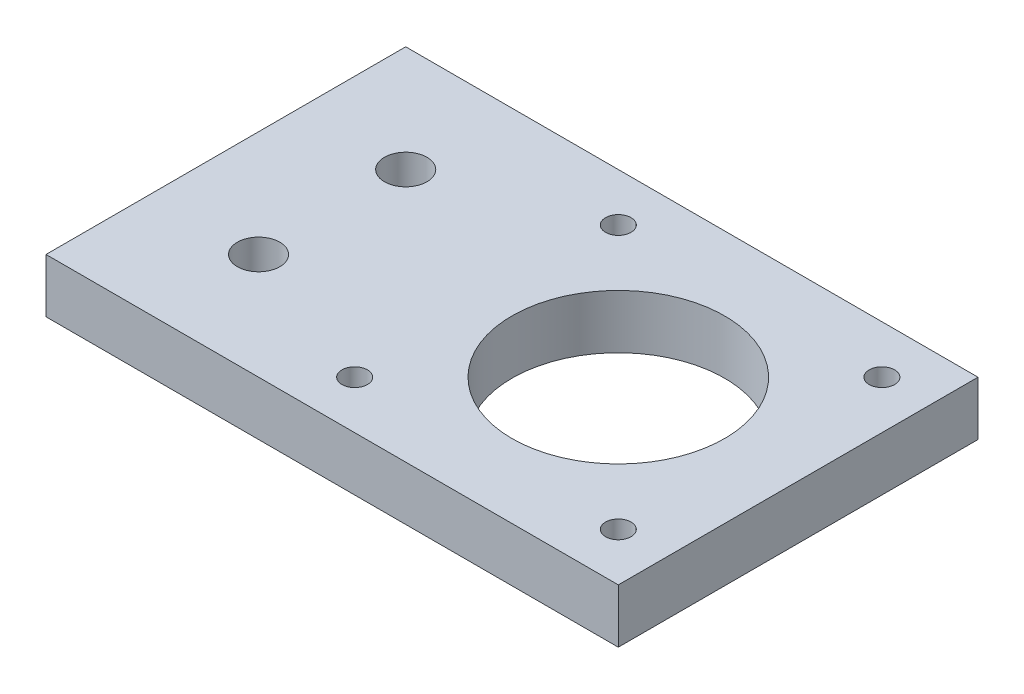
SolidWorks part; units mm, degrees
ref_plane "Front Plane" through (0, 0, 0) normal (0, 0, 1) x (1, 0, 0)
ref_plane "Top Plane" through (0, 0, 0) normal (0, 1, 0) x (1, 0, 0)
ref_plane "Right Plane" through (0, 0, 0) normal (1, 0, 0) x (0, 0, -1)
other "Default"
sketch "Sketch1" plane through (0, 0, 0) normal (0, 1, 0) x (1, 0, 0)
  line L0 (-33.65, 21.15) -> (-33.65, 8.65) construction
  line L1 (-46.15, -21.15) -> (21.15, -21.15)
  line L2 (-46.15, -21.15) -> (-46.15, 21.15)
  line L3 (-46.15, 21.15) -> (21.15, 21.15)
  line L4 (21.15, -21.15) -> (21.15, 21.15)
  line L5 (-15.5, -15.5) -> (15.5, -15.5) construction
  line L6 (-15.5, -15.5) -> (-15.5, 15.5) construction
  line L7 (-15.5, 15.5) -> (15.5, 15.5) construction
  line L8 (15.5, -15.5) -> (15.5, 15.5) construction
  line L9 (-15.5, -15.5) -> (15.5, 15.5) construction
  line L10 (-15.5, 15.5) -> (15.5, -15.5) construction
  line L11 (-33.65, -8.65) -> (-33.65, -21.15) construction
  line L12 (-21.15, 0) -> (-46.15, 0) construction
  line L13 (-33.65, -8.65) -> (-46.15, -8.65) construction
  circle A0 centre (15.5, -15.5) radius 1.5
  circle A1 centre (15.5, 15.5) radius 1.5
  circle A2 centre (-15.5, 15.5) radius 1.5
  circle A3 centre (-15.5, -15.5) radius 1.5
  circle A4 centre (0, 0) radius 12.5
  circle A5 centre (0, 0) radius 21.15 construction
  circle A6 centre (-33.65, 8.65) radius 2.5
  circle A7 centre (-33.65, -8.65) radius 2.5
  point P4 (0, 0)
  point P14 (21.15, 0)
  point P15 (-21.15, 0)
  point P27 (-33.65, 0)
  dimension "MountingDiameter" = 3
  dimension "SpinningDiameter" = 25
  dimension "ClearanceDiameter" = 42.3
  dimension "AluminumMountingDiameter" = 5
  dimension "HoleSeparation" = 31
  dimension "Height" = 42.3
  dimension "Clearance" = 25
extrude "Boss-Extrude1" add sketch "Sketch1" along normal mid plane 6.35
